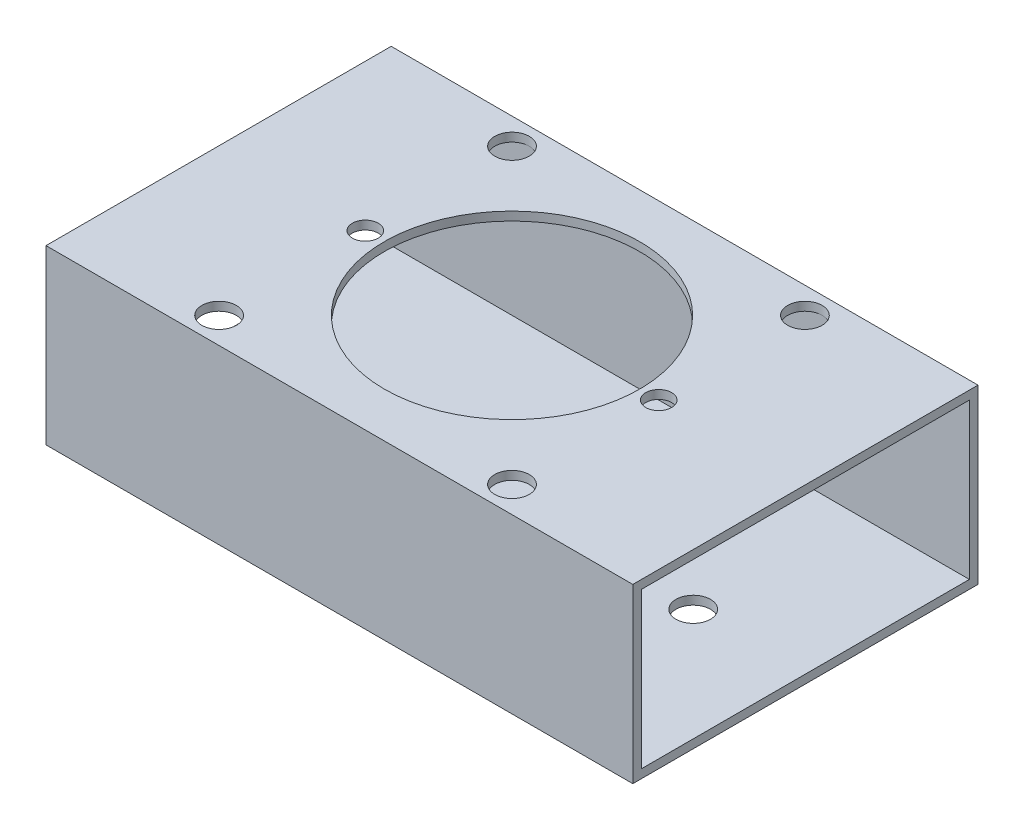
SolidWorks part; units mm, degrees
ref_plane "前视基准面" through (0, 0, 0) normal (0, 0, 1) x (1, 0, 0)
ref_plane "上视基准面" through (0, 0, 0) normal (0, 1, 0) x (1, 0, 0)
ref_plane "右视基准面" through (0, 0, 0) normal (1, 0, 0) x (0, 0, -1)
sketch "草图1" plane through (0, 0, 0) normal (0, 1, 0) x (1, 0, 0)
  line L0 (-34, -20) -> (34, -20)
  line L1 (-34, -20) -> (-34, 20)
  line L2 (34, -20) -> (34, 20)
  line L3 (-34, 20) -> (34, 20)
  line L4 (-34, -20) -> (34, 20) construction
  line L5 (34, -20) -> (-34, 20) construction
  point P1 (0, 0)
  dimension "D1" = 40
  dimension "D2" = 68
extrude "凸台-拉伸1" add sketch "草图1" along normal blind 20
sketch "草图2" plane through (34, 0, 0) normal (1, 0, 0) x (0, 0, -1)
  line L0 (-19, 19) -> (-19, 1)
  line L1 (-19, 1) -> (19, 1)
  line L2 (19, 1) -> (19, 19)
  line L3 (19, 19) -> (-19, 19)
  line L4 (-20, 0) -> (20, 0)
  line L5 (20, 0) -> (20, 20)
  line L6 (20, 20) -> (-20, 20)
  line L7 (-20, 20) -> (-20, 0)
  line L8 (-20, 0) -> (20, 0)
  line L9 (20, 0) -> (20, 20)
  line L10 (20, 20) -> (-20, 20)
  line L11 (-20, 20) -> (-20, 0)
  dimension "D1" = 0
  dimension "D2" = 1
extrude "切除-拉伸1" cut sketch "草图2" against normal through all contours L3 L0 L1 L2
sketch "草图3" plane through (0, 0, 0) normal (0, -1, 0) x (1, 0, 0)
  line L0 (0, 0) -> (21, 0)
  line L1 (0, 0) -> (-21, 0)
  circle A0 centre (-21, 0) radius 2
  circle A1 centre (21, 0) radius 2
  dimension "D1" = 21
  dimension "D2" = 21
extrude "切除-拉伸2" cut sketch "草图3" against normal blind 1 contours A0 | A1
sketch "草图4" plane through (0, 20, 0) normal (0, 1, 0) x (1, 0, 0)
  circle A0 centre (0, 0) radius 14.8
  circle A1 centre (0, 0) radius 17
  circle A2 centre (17, 0) radius 1.5
  circle A3 centre (-17, 0) radius 1.5
extrude "切除-拉伸3" cut sketch "草图4" against normal blind 1 contours A0 | A3 | A2
sketch "草图5" plane through (0, 20, 0) normal (0, 1, 0) x (1, 0, 0)
  line L0 (16.9706, 16.9706) -> (-16.9706, 16.9706)
  line L1 (16.9706, 16.9706) -> (16.9706, -16.9706)
  line L2 (-16.9706, 16.9706) -> (-16.9706, -16.9706)
  line L3 (16.9706, -16.9706) -> (-16.9706, -16.9706)
  line L4 (16.9706, 16.9706) -> (-16.9706, -16.9706) construction
  line L5 (-16.9706, 16.9706) -> (16.9706, -16.9706) construction
  point P0 (0, 0)
  point P1 (0, 0)
  dimension "D1" = 48
  dimension "D2" = 48
hole_wizard "大小mm Press 暗销孔1" positions "3D草图1" profile "草图6" hole size "Ø4.0" standard "ANSI Metric"
sketch3d "3D草图1"
  point P0 (16.9706, 20, 16.9706)
  point P3 (-16.9706, 20, 16.9706)
  point P6 (-16.9706, 20, -16.9706)
  point P9 (16.9706, 20, -16.9706)
sketch "草图6" plane through (16.9706, 20, 16.9706) normal (1, 0, 0) x (0, 0, 1)
  line L0 (0, 0) -> (0, 2.2017)
  line L1 (0, 2.2017) -> (2, 1)
  line L2 (2, 1) -> (2, 0)
  line L5 (2, 0) -> (0, 0)
  line L10 (0, 2.2017) -> (-2, 1) construction
  line L11 (0, -6.35) -> (0, 107.95) construction
  dimension "孔直径" = 4
  dimension "孔深度" = 1
  dimension "导头角度" = 118
